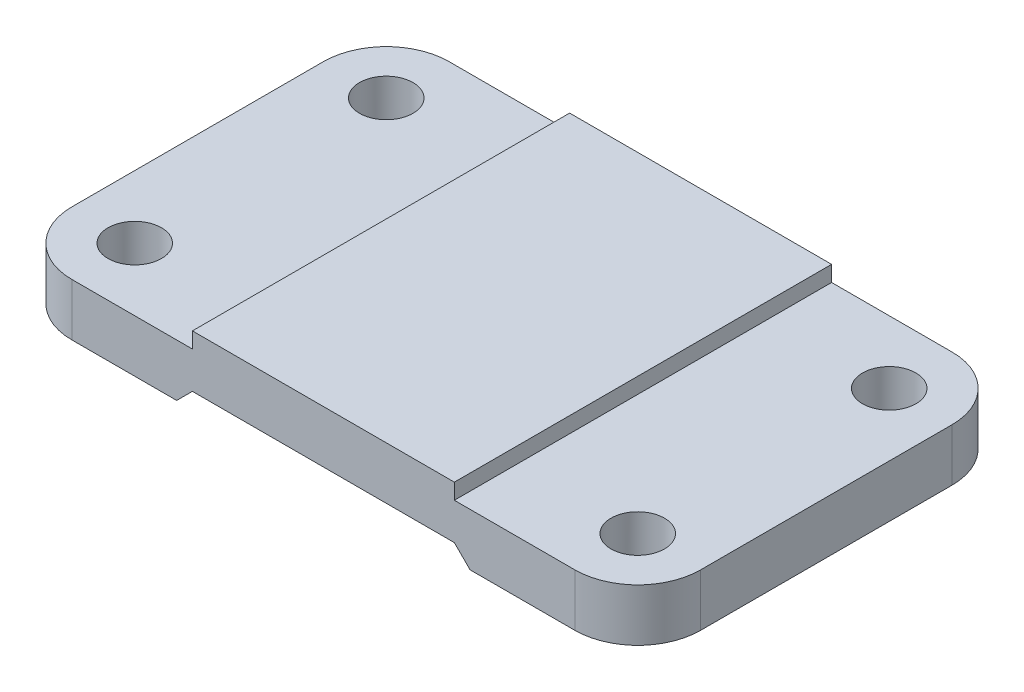
SolidWorks part; units mm, degrees
ref_plane "Front Plane" through (0, 0, 0) normal (0, 0, 1) x (1, 0, 0)
ref_plane "Top Plane" through (0, 0, 0) normal (0, 1, 0) x (1, 0, 0)
ref_plane "Right Plane" through (0, 0, 0) normal (1, 0, 0) x (0, 0, -1)
sketch "Sketch1" plane through (0, 0, 0) normal (0, 1, 0) x (1, 0, 0)
  line L0 (0, 80.4695) -> (0, -82.3629) construction
  line L1 (-112.8466, 0) -> (122.6923, 0) construction
  line L2 (-25, 36) -> (-25, -36)
  line L4 (25, 36) -> (-25, 36)
  line L10 (-25, -36) -> (25, -36)
  line L11 (25, -36) -> (25, 36)
  dimension "D1" = 72
  dimension "D2" = 50
extrude "Boss-Extrude1" add sketch "Sketch1" along normal blind 10
sketch "Sketch3" plane through (0, 0, 0) normal (0, 0, 1) x (1, 0, 0)
  line L0 (-25, 10) -> (25, 10) construction
  line L1 (-25, 10) -> (-25, 0) construction
  line L2 (-25, 7) -> (-60, 7)
  line L3 (-60, 7) -> (-60, -3)
  line L4 (-60, -3) -> (-28, -3)
  line L5 (25, 7) -> (60, 7)
  line L6 (-28, -3) -> (-25, 0)
  line L7 (25, 10) -> (25, 0) construction
  line L8 (60, 7) -> (60, -3)
  line L9 (60, -3) -> (28, -3)
  line L10 (25, 0) -> (28, -3)
  line L11 (-25, 0) -> (25, 0) construction
  line L12 (-25, 0) -> (-25, 7)
  line L13 (25, 0) -> (25, 7)
  dimension "D1" = 3
  dimension "D2" = 35
  dimension "D3" = 10
  dimension "D4" = 3
  dimension "D5" = 45
extrude "Boss-Extrude2" add sketch "Sketch3" along normal mid plane 72
sketch "Sketch4" plane through (0, 0, 0) normal (0, 1, 0) x (1, 0, 0)
  line L0 (0, 44.4892) -> (0, -51.789) construction
  line L1 (-69.052, 0) -> (68.6575, 0) construction
  circle A0 centre (-48, 24) radius 5.1
  circle A1 centre (-48, -24) radius 5.1
  circle A2 centre (48, 24) radius 5.1
  circle A3 centre (48, -24) radius 5.1
  dimension "D1" = 10.2
  dimension "D2" = 10.2
  dimension "D3" = 10.2
  dimension "D4" = 10.2
  dimension "D5" = 24
  dimension "D6" = 48
extrude "Cut-Extrude1" cut sketch "Sketch4" against normal mid plane 72
fillet "Fillet1" radius 12 1 edges at (-60, 2, -36)
fillet "Fillet2" radius 12 1 edges at (-60, 2, 36)
fillet "Fillet3" radius 12 2 edges at (60, 2, -36) (60, 2, 36)
